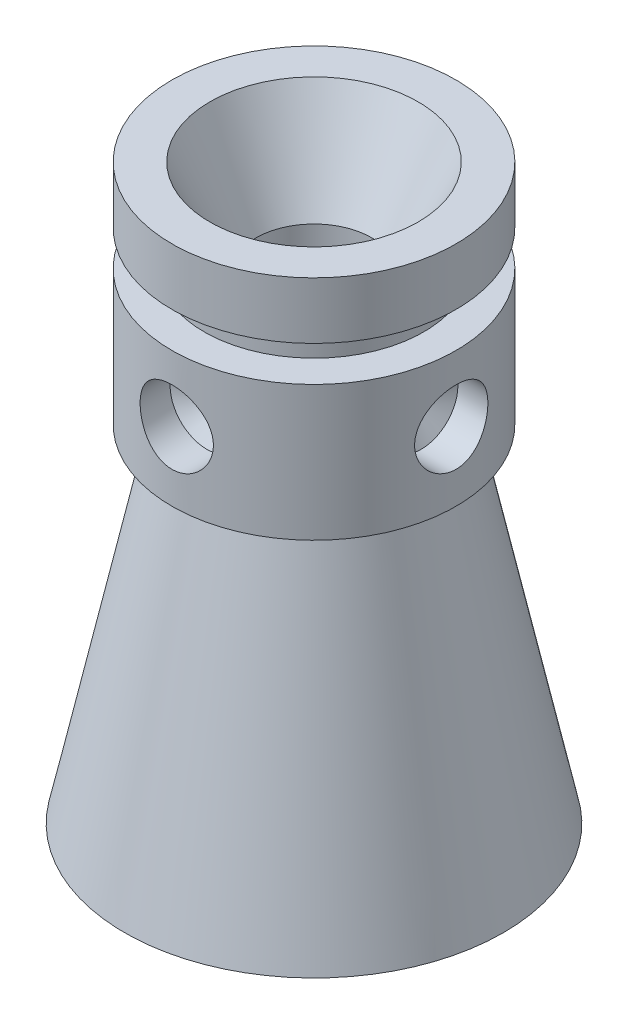
SolidWorks part; units mm, degrees
material "AISI 316 Annealed Stainless Steel Bar (SS)"
ref_plane "Front Plane" through (0, 0, 0) normal (0, 0, 1) x (1, 0, 0)
ref_plane "Top Plane" through (0, 0, 0) normal (0, 1, 0) x (1, 0, 0)
ref_plane "Right Plane" through (0, 0, 0) normal (1, 0, 0) x (0, 0, -1)
sketch "Sketch1" plane through (0, 0, 0) normal (0, 0, 1) x (1, 0, 0)
  line L20 (0, 0) -> (-9.525, 0) construction
  line L21 (0, 0) -> (0, -38.4163) construction
  line L37 (-6.424, -6.35) -> (-6.424, -8.89) construction
  line L38 (-6.424, -8.89) -> (-12.7, -38.4163) construction
  line L39 (-3.884, -6.35) -> (-3.884, 0) construction
  line L40 (-12.7, -38.4163) -> (-10.16, -38.4163)
  line L41 (-10.16, -38.4163) -> (-3.884, -8.89)
  line L42 (-3.884, -8.89) -> (-6.424, -8.89) construction
  line L43 (-3.884, -8.89) -> (-3.884, -6.35)
  line L46 (-10.16, -38.4163) -> (0, -38.4163) construction
  line L48 (-6.985, 0) -> (-3.884, -6.35)
  line L55 (-3.884, -6.35) -> (-9.525, -6.35) construction
  line L56 (-6.985, 0) -> (-9.525, 0)
  line L57 (-9.525, 0) -> (-9.525, -15.24) construction
  line L58 (-9.525, -3.81) -> (-7.366, -3.81)
  line L59 (-7.366, -3.81) -> (-7.366, -6.1913)
  line L60 (-7.366, -6.1913) -> (-9.525, -6.1913)
  line L61 (-9.525, 0) -> (-9.525, -3.81)
  line L63 (-9.525, -6.1913) -> (-9.525, -15.24)
  line L64 (-9.525, -15.24) -> (-7.7737, -15.24)
  line L65 (-12.7, -38.4163) -> (-7.7737, -15.24)
  dimension "D1" = 9.525
  dimension "D2" = 2.54
  dimension "D3" = 15.24
  dimension "D4" = 2.54
  dimension "D5" = 3.884
  dimension "D6" = 2.54
  dimension "D7" = 12
  dimension "D8" = 10.16
  dimension "D9" = 3.81
  dimension "D10" = 2.3813
  dimension "D11" = 7.366
  dimension "D12" = 6.35
revolve "Body" add sketch "Sketch1" angle 360 about L21
ref_plane "HolePlane" through (-9.525, 0, 0) normal (-1, 0, 0) x (0, 0, 1)
sketch "Sketch3" plane through (-9.525, 0, 0) normal (-1, 0, 0) x (0, 0, 1)
  line L0 (0, 0) -> (0, -10.6363)
  line L1 (9.525, -6.1912) -> (-9.525, -6.1912) construction
  point P6 (0, -10.6363)
  dimension "D1" = 4.445
hole_wizard "SetScrew" positions "Sketch3" profile "Sketch4" hole size "#10" standard "ANSI Inch"
sketch "Sketch4" plane through (-9.525, -10.6363, 0) normal (0, 1, 0) x (0, 0, 1)
  line L0 (0, 0) -> (0, 3.81)
  line L1 (0, 3.81) -> (2.4574, 2.3334)
  line L2 (2.4574, 2.3334) -> (2.4574, 0)
  line L5 (2.4574, 0) -> (0, 0)
  line L10 (0, 3.81) -> (-2.4574, 2.3334) construction
  line L11 (0, -6.35) -> (0, 107.95) construction
  dimension "Hole Dia." = 4.9149
  dimension "Hole Depth" = 3.81
  dimension "Drill Angle" = 118
pattern_circular "CirPattern1" count 4 over 360 about axis through (0, 0, 0) along (0, 1, 0) of "SetScrew"
equation "\"dt\"=0.1"
equation "\"w\"=0.1"
